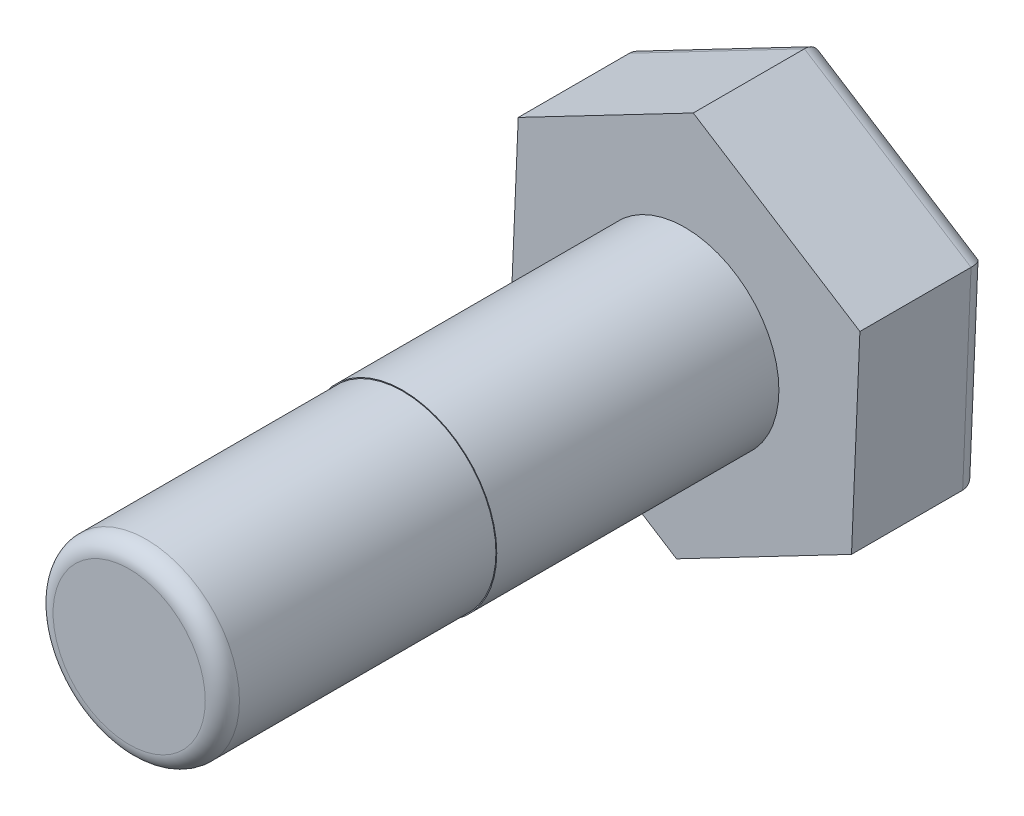
SolidWorks part; units mm, degrees
ref_plane "前视" through (0, 0, 0) normal (0, 0, 1) x (1, 0, 0)
ref_plane "上视" through (0, 0, 0) normal (0, 1, 0) x (1, 0, 0)
ref_plane "右视" through (0, 0, 0) normal (1, 0, 0) x (0, 0, -1)
sketch "草图1" plane through (0, 0, 0) normal (0, 0, 1) x (1, 0, 0)
  line L1 (20.4724, 10.6871) -> (0.9809, 23.0732)
  line L2 (0.9809, 23.0732) -> (-19.4915, 12.3861)
  line L3 (-19.4915, 12.3861) -> (-20.4724, -10.6871)
  line L4 (-20.4724, -10.6871) -> (-0.9809, -23.0732)
  line L5 (-0.9809, -23.0732) -> (19.4915, -12.3861)
  line L6 (19.4915, -12.3861) -> (20.4724, 10.6871)
  circle A0 centre (0, 0) radius 20 construction
  dimension "D1" = 40
extrude "基体-拉伸" add sketch "草图1" along normal blind 15
sketch "草图2" plane through (0, 0, 15) normal (0, 0, 1) x (1, 0, 0)
  circle A0 centre (0, 0) radius 11
  dimension "D1" = 22
extrude "凸台-拉伸1" add sketch "草图2" along normal blind 33
fillet "圆角3" radius 2 6 edges at (9.2553, -17.7296, 0) (-10.7266, -16.8801, 0) (-19.982, 0.8495, 0) (-9.2553, 17.7296, 0) (10.7266, 16.8801, 0) (19.982, -0.8495, 0)
sketch "草图3" plane through (0, 0, 48) normal (0, 0, 1) x (1, 0, 0)
  circle A0 centre (0, 0) radius 10.9
extrude "拉伸1" add sketch "草图3" along normal blind 32
fillet "圆角4" radius 2 1 edges at (10.9, 0, 80)
